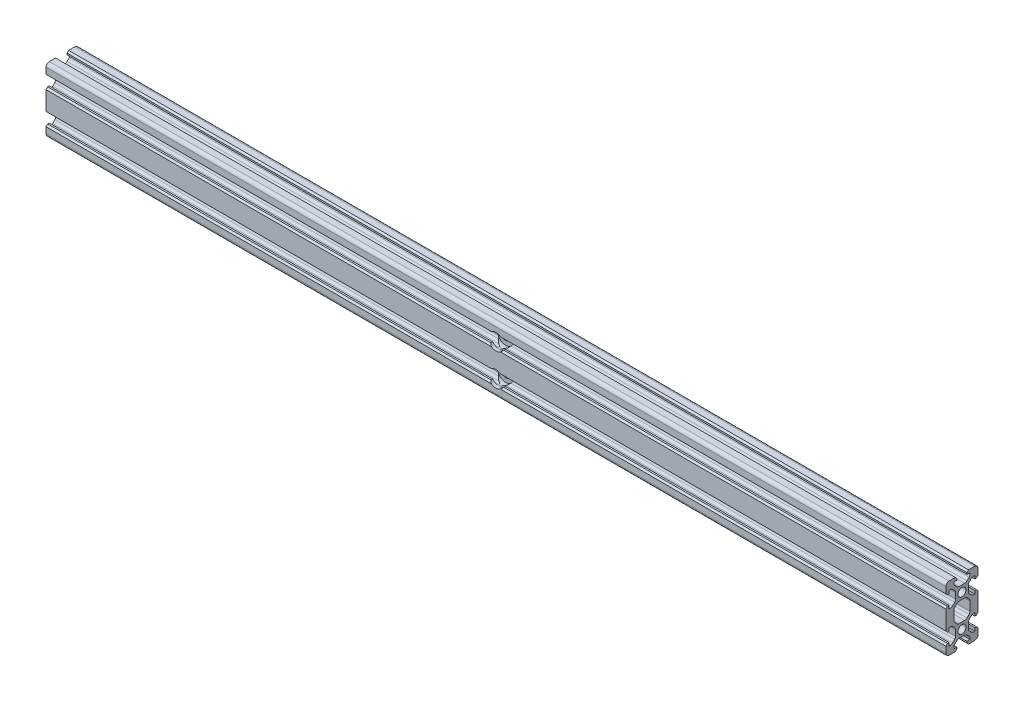
SolidWorks part; units mm, degrees
ref_plane "Front Plane" through (0, 0, 0) normal (0, 0, 1) x (1, 0, 0)
ref_plane "Top Plane" through (0, 0, 0) normal (0, 1, 0) x (1, 0, 0)
ref_plane "Right Plane" through (0, 0, 0) normal (1, 0, 0) x (0, 0, -1)
sketch "Sketch1" plane through (0, 0, 0) normal (1, 0, 0) x (0, 0, -1)
  line B0 (6.9, 38) -> (5, 38)
  line B1 (19, 6.9) -> (20, 5.9)
  line B2 (14.4142, 15.8284) -> (13.1236, 14.5379)
  line B3 (20, 14.1) -> (19, 13.1)
  line B4 (15.8284, 5.5858) -> (14.5379, 6.8764)
  line B5 (17.2426, 5) -> (18, 5)
  line B6 (18, 6.9) -> (18, 5)
  line B7 (17.2426, 15) -> (18, 15)
  line B8 (8.2906, 13.9521) -> (11.7094, 13.9521)
  line B9 (18, 15) -> (18, 13.1)
  line B10 (18, 13.1) -> (19, 13.1)
  line B11 (18, 6.9) -> (19, 6.9)
  line B12 (13.9521, 11.7094) -> (13.9521, 8.2906)
  line B13 (6.8764, 14.5379) -> (5.5858, 15.8284)
  line B14 (20, 5.9) -> (20, 2)
  line B15 (14.5379, 13.1236) -> (15.8284, 14.4142)
  line B16 (6.9, 1) -> (5.9, 0)
  line B17 (18, 0) -> (14.1, 0)
  line B18 (14.1, 0) -> (13.1, 1)
  line B19 (5.5858, 4.1716) -> (6.8764, 5.4621)
  line B20 (5, 2.7574) -> (5, 2)
  line B21 (6.9, 2) -> (5, 2)
  line B22 (15, 2.7574) -> (15, 2)
  line B23 (15, 2) -> (13.1, 2)
  line B24 (13.1, 2) -> (13.1, 1)
  line B25 (6.9, 2) -> (6.9, 1)
  line B26 (11.7094, 6.0479) -> (8.2906, 6.0479)
  line B27 (5.9, 0) -> (2, 0)
  line B28 (13.1236, 5.4621) -> (14.4142, 4.1716)
  line B29 (1, 13.1) -> (0, 14.1)
  line B30 (0, 2) -> (0, 5.9)
  line B31 (0, 5.9) -> (1, 6.9)
  line B32 (4.1716, 14.4142) -> (5.4621, 13.1236)
  line B33 (2.7574, 15) -> (2, 15)
  line B34 (2, 13.1) -> (2, 15)
  line B35 (2.7574, 5) -> (2, 5)
  line B36 (2, 5) -> (2, 6.9)
  line B37 (2, 6.9) -> (1, 6.9)
  line B38 (2, 13.1) -> (1, 13.1)
  line B39 (6.0479, 8.2906) -> (6.0479, 11.7094)
  line B40 (5.4621, 6.8764) -> (4.1716, 5.5858)
  line B41 (19, 26.9) -> (20, 25.9)
  line B42 (15, 38) -> (13.1, 38)
  line B43 (14.1, 40) -> (13.1, 39)
  line B44 (14.4142, 35.8284) -> (13.1236, 34.5379)
  line B45 (18, 35) -> (18, 33.1)
  line B46 (6.9, 38) -> (6.9, 39)
  line B47 (18, 40) -> (14.1, 40)
  line B48 (5.9, 40) -> (2, 40)
  line B49 (0, 25.9) -> (1, 26.9)
  line B50 (17.2426, 25) -> (18, 25)
  line B51 (5, 37.2426) -> (5, 38)
  line B52 (18, 26.9) -> (19, 26.9)
  line B53 (13.1, 38) -> (13.1, 39)
  line B54 (2, 26.9) -> (1, 26.9)
  line B55 (20, 34.1) -> (19, 33.1)
  line B56 (5, 22.7574) -> (5, 17.2426)
  line B57 (20, 34.1) -> (20, 38)
  line B58 (0, 38) -> (0, 34.1)
  line B59 (13.1236, 25.4621) -> (14.4142, 24.1716)
  line B60 (2, 25) -> (2, 26.9)
  line B61 (6.0479, 28.2906) -> (6.0479, 31.7094)
  line B62 (18, 33.1) -> (19, 33.1)
  line B63 (15, 37.2426) -> (15, 38)
  line B64 (2, 33.1) -> (2, 35)
  line B65 (18, 26.9) -> (18, 25)
  line B66 (11.7094, 26.0479) -> (8.2906, 26.0479)
  line B67 (17.2426, 35) -> (18, 35)
  line B68 (20, 25.9) -> (20, 14.1)
  line B69 (1, 33.1) -> (0, 34.1)
  line B70 (14.5379, 33.1236) -> (15.8284, 34.4142)
  line B71 (4.1716, 34.4142) -> (5.4621, 33.1236)
  line B72 (13.9521, 31.7094) -> (13.9521, 28.2906)
  line B73 (2.7574, 35) -> (2, 35)
  line B74 (8.2906, 33.9521) -> (11.7094, 33.9521)
  line B75 (6.9, 39) -> (5.9, 40)
  line B76 (5.4621, 26.8764) -> (4.1716, 25.5858)
  line B77 (0, 14.1) -> (0, 25.9)
  line B78 (5.5858, 24.1716) -> (6.8764, 25.4621)
  line B79 (15.8284, 25.5858) -> (14.5379, 26.8764)
  line B80 (6.8764, 34.5379) -> (5.5858, 35.8284)
  line B81 (15, 22.7574) -> (15, 17.2426)
  line B82 (2.7574, 25) -> (2, 25)
  line B83 (2, 33.1) -> (1, 33.1)
  circle B84 centre (10, 10) radius 2.5
  arc B85 (5.4621, 13.1236) -> (6.0479, 11.7094) centre (4.0479, 11.7094) cw
  arc B86 (4.1716, 14.4142) -> (2.7574, 15) centre (2.7574, 13) ccw
  arc B87 (5, 17.2426) -> (5.5858, 15.8284) centre (7, 17.2426) ccw
  arc B88 (15, 17.2426) -> (14.4142, 15.8284) centre (13, 17.2426) cw
  arc B89 (17.2426, 15) -> (15.8284, 14.4142) centre (17.2426, 13) ccw
  arc B90 (15.8284, 5.5858) -> (17.2426, 5) centre (17.2426, 7) ccw
  arc B91 (15, 2.7574) -> (14.4142, 4.1716) centre (13, 2.7574) ccw
  arc B92 (5.5858, 4.1716) -> (5, 2.7574) centre (7, 2.7574) ccw
  arc B93 (2.7574, 5) -> (4.1716, 5.5858) centre (2.7574, 7) ccw
  arc B94 (6.0479, 8.2906) -> (5.4621, 6.8764) centre (4.0479, 8.2906) cw
  arc B95 (6.8764, 5.4621) -> (8.2906, 6.0479) centre (8.2906, 4.0479) cw
  arc B96 (11.7094, 6.0479) -> (13.1236, 5.4621) centre (11.7094, 4.0479) cw
  arc B97 (14.5379, 6.8764) -> (13.9521, 8.2906) centre (15.9521, 8.2906) cw
  arc B98 (13.9521, 11.7094) -> (14.5379, 13.1236) centre (15.9521, 11.7094) cw
  arc B99 (11.7094, 13.9521) -> (13.1236, 14.5379) centre (11.7094, 15.9521) ccw
  arc B100 (8.2906, 13.9521) -> (6.8764, 14.5379) centre (8.2906, 15.9521) cw
  arc B101 (2, 0) -> (0, 2) centre (2, 2) cw
  arc B102 (20, 2) -> (18, 0) centre (18, 2) cw
  arc B103 (11.7094, 26.0479) -> (13.1236, 25.4621) centre (11.7094, 24.0479) cw
  arc B104 (13.9521, 31.7094) -> (14.5379, 33.1236) centre (15.9521, 31.7094) cw
  arc B105 (14.5379, 26.8764) -> (13.9521, 28.2906) centre (15.9521, 28.2906) cw
  arc B106 (5.5858, 24.1716) -> (5, 22.7574) centre (7, 22.7574) ccw
  arc B107 (5, 37.2426) -> (5.5858, 35.8284) centre (7, 37.2426) ccw
  arc B108 (11.7094, 33.9521) -> (13.1236, 34.5379) centre (11.7094, 35.9521) ccw
  arc B109 (15, 22.7574) -> (14.4142, 24.1716) centre (13, 22.7574) ccw
  arc B110 (2.7574, 25) -> (4.1716, 25.5858) centre (2.7574, 27) ccw
  arc B111 (15, 37.2426) -> (14.4142, 35.8284) centre (13, 37.2426) cw
  circle B112 centre (10, 30) radius 2.5
  arc B113 (8.2906, 33.9521) -> (6.8764, 34.5379) centre (8.2906, 35.9521) cw
  arc B114 (6.0479, 28.2906) -> (5.4621, 26.8764) centre (4.0479, 28.2906) cw
  arc B115 (6.8764, 25.4621) -> (8.2906, 26.0479) centre (8.2906, 24.0479) cw
  arc B116 (4.1716, 34.4142) -> (2.7574, 35) centre (2.7574, 33) ccw
  arc B117 (15.8284, 25.5858) -> (17.2426, 25) centre (17.2426, 27) ccw
  arc B118 (5.4621, 33.1236) -> (6.0479, 31.7094) centre (4.0479, 31.7094) cw
  arc B119 (2, 40) -> (0, 38) centre (2, 38) ccw
  arc B120 (17.2426, 35) -> (15.8284, 34.4142) centre (17.2426, 33) ccw
  arc B121 (20, 38) -> (18, 40) centre (18, 38) ccw
sketch_block_instance "2040-1"
sketch_block "2040" parameters "D1"=2, "D2"=2
extrude "Boss-Extrude1" add sketch "Sketch1" along normal blind 560
sketch "Sketch2" plane through (0, 0, 0) normal (0, 0, 1) x (1, 0, 0)
  line L0 (280, 34.1) -> (280, 25.9) construction
  line L3 (560, 34.1) -> (0, 34.1) construction
  line L4 (560, 25.9) -> (0, 25.9) construction
  line L5 (280, 14.1) -> (280, 5.9) construction
  line L6 (560, 14.1) -> (0, 14.1) construction
  line L7 (560, 5.9) -> (0, 5.9) construction
  circle A0 centre (280, 30) radius 2.5
  circle A1 centre (280, 10) radius 2.5
extrude "Cut-Extrude1" cut sketch "Sketch2" against normal through all
sketch "Sketch3" plane through (0, 0, 0) normal (0, 0, 1) x (1, 0, 0)
  circle A0 centre (280, 30) radius 5
  circle A1 centre (280, 10) radius 5
extrude "Cut-Extrude2" cut sketch "Sketch3" against normal blind 6.1
